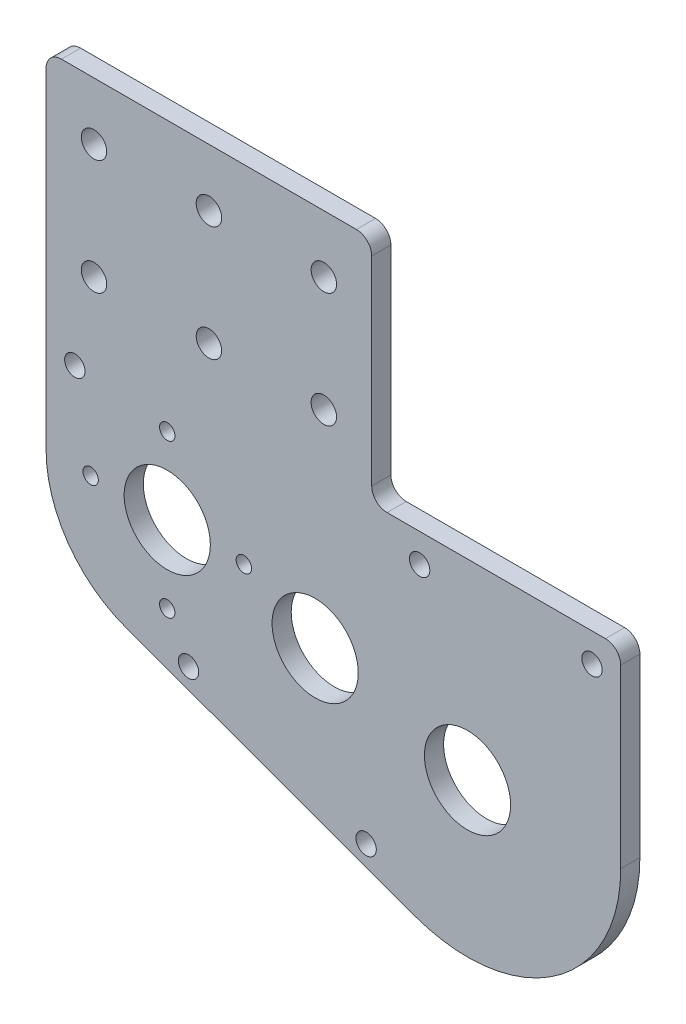
SolidWorks part; units mm, degrees
ref_plane "Front Plane" through (0, 0, 0) normal (0, 0, 1) x (1, 0, 0)
ref_plane "Top Plane" through (0, 0, 0) normal (0, 1, 0) x (1, 0, 0)
ref_plane "Right Plane" through (0, 0, 0) normal (1, 0, 0) x (0, 0, -1)
sketch "Gear&Motor Layout" plane through (0, 0, 0) normal (0, 0, 1) x (1, 0, 0)
  line L1 (-139.7, 63.5) -> (50.8, 63.5) construction
  line L2 (-99.5384, 24.9428) -> (0, 0) construction
  circle A1 centre (-99.5384, 24.9428) radius 32.2072 construction
  circle A2 centre (0, 0) radius 14.2875 construction
  circle A3 centre (-99.5384, 24.9428) radius 25.4 construction
  circle A4 centre (-124.9384, 24.9428) radius 2.5527 construction
  circle A5 centre (-99.5384, 50.3428) radius 2.5527 construction
  circle A6 centre (-74.1384, 24.9428) radius 2.5527 construction
  circle A7 centre (-99.5384, -0.4572) radius 2.5527 construction
  circle A11 centre (-50.5084, 12.6566) radius 41.91 construction
  circle A12 centre (-50.5084, 12.6566) radius 43.18 construction
  circle A15 centre (0, 0) radius 38.1 construction
  circle A16 centre (0, 0) radius 39.37 construction
  circle A17 centre (-50.5084, 12.6566) radius 13.97 construction
  circle A18 centre (-50.5084, 12.6566) radius 15.24 construction
  circle A20 centre (-99.5384, 24.9428) radius 8.89 construction
  arc A22 (-103.5384, 24.9428) -> (-95.5384, 24.9428) centre (-99.5384, 24.9428) ccw construction
  point P5 (-124.9384, 24.9428)
  point P8 (-99.5384, 50.3428)
  point P10 (-74.1384, 24.9428)
  point P14 (-99.5384, -0.4572)
  point P29 (-98.4907, 24.9428)
  point P30 (0, 0)
  point P31 (0, 0)
  point P35 (0, 0)
  point P39 (0, 0)
  point P40 (-93.0804, 49.5081)
  point P41 (0, 0)
  point P42 (0, 0)
  dimension "D4" = 83.82
  dimension "D1" = 28.575
  dimension "D3" = 50.8
  dimension "D6" = 17.78
  dimension "D7" = 86.36
  dimension "D8" = 27.94
  dimension "D9" = 30.48
  dimension "D10" = 76.2
  dimension "D11" = 78.74
  dimension "D13" = 63.5
  dimension "D14" = 5.1054
  dimension "D16" = 6.35
  dimension "D12" = 50.8
  dimension "D15" = 190.5
sketch "Sketch2" plane through (0, 0, 0) normal (0, 0, 1) x (1, 0, 0)
  line L0 (50.8, 63.5) -> (-139.7, 63.5)
  line L1 (50.8, 63.5) -> (50.8, 0)
  line L2 (-17.39, -47.7308) -> (-113.2866, -12.7923)
  line L3 (-139.7, 24.9428) -> (-139.7, 63.5)
  arc A0 (50.8, 0) -> (-17.39, -47.7308) centre (0, 0) cw
  arc A1 (-113.2866, -12.7923) -> (-139.7, 24.9428) centre (-99.5384, 24.9428) cw
extrude "Boss-Extrude1" add sketch "Sketch2" against normal blind 6.35
sketch "Sketch3" plane through (0, 0, 0) normal (0, 0, 1) x (1, 0, 0)
  line L0 (-139.7, 63.5) -> (-139.7, 139.7)
  line L1 (-139.7, 139.7) -> (-31.75, 139.7)
  line L2 (-31.75, 139.7) -> (-31.75, 63.5)
  line L5 (50.8, 0) -> (50.8, 63.5) construction
  line L6 (50.8, 63.5) -> (-139.7, 63.5) construction
  line L7 (-31.75, 63.5) -> (-139.7, 63.5)
  dimension "D1" = 82.55
  dimension "D2" = 76.2
extrude "Boss-Extrude2" add sketch "Sketch3" against normal up to surface (6.35 mm away) up to face at (-50.333, 11.5841, -6.35)
fillet "Fillet1" radius 5.08 4 edges at (50.8, 63.5, -3.175) (-31.75, 63.5, -3.175) (-31.75, 139.7, -3.175) (-139.7, 139.7, -3.175)
sketch "Sketch4" plane through (0, 0, 0) normal (0, 0, 1) x (1, 0, 0)
  circle A0 centre (0, 0) radius 14.2875 construction
  circle A1 centre (0, 0) radius 14.2875
  circle A2 centre (-50.5084, 12.6566) radius 14.2875
  circle A3 centre (-99.5384, 24.9428) radius 14.2875
  arc A4 (-103.0384, 24.9428) -> (-96.0384, 24.9428) centre (-99.5384, 24.9428) ccw construction
  point P9 (0, 0)
  dimension "D1" = 28.575
extrude "Cut-Extrude1" cut sketch "Sketch4" against normal up to next
hole_wizard "#10 Clearance Hole1" positions "Gear&Motor Layout" profile "Sketch6" hole size "#10" standard "ANSI Inch" end condition through all
sketch "Sketch6" plane through (-99.5384, -0.4572, 0) normal (1, 0, 0) x (0, -1, 0)
  line L0 (0, 0) -> (0, 6.35)
  line L1 (0, 6.35) -> (2.5527, 6.35)
  line L2 (2.5527, 6.35) -> (2.5527, 0)
  line L5 (2.5527, 0) -> (0, 0)
  line L11 (0, -6.35) -> (0, 107.95) construction
  dimension "Thru Hole Dia." = 5.1054
  dimension "Thru Hole Depth" = 6.35
hole_wizard "1/4 Clearance Hole1" positions "Sketch11" profile "Sketch9" hole size "1/4" standard "ANSI Inch" end condition through all
sketch "Sketch11" plane through (0, 0, 0) normal (0, 0, 1) x (1, 0, 0)
  line L0 (50.8, 0) -> (50.8, 58.42) construction
  line L1 (-139.7, 63.5) -> (50.8, 63.5) construction
  line L2 (-92.4826, -13.6136) -> (-33.6126, -35.062) construction
  line L4 (-113.2866, -12.7923) -> (-17.39, -47.7308) construction
  line L5 (-33.6126, -35.062) -> (-30.0888, -25.3901) construction
  line L6 (-89.5962, -5.6914) -> (-92.4826, -13.6136) construction
  line L7 (-139.7, 134.62) -> (-139.7, 24.9428) construction
  circle A0 centre (-50.5084, 12.6566) radius 43.18 construction
  circle A1 centre (0, 0) radius 39.37 construction
  circle A2 centre (-99.5384, 24.9428) radius 32.2072 construction
  point P0 (-33.6126, -35.062)
  point P2 (-92.4826, -13.6136)
  point P4 (-130.175, 53.975)
  point P6 (-15.875, 53.975)
  point P8 (41.275, 53.975)
  dimension "D1" = 9.525
  dimension "D2" = 9.525
  dimension "D3" = 6.35
  dimension "2" = 57.15
  dimension "D4" = 9.525
  dimension "D5" = 9.525
sketch "Sketch9" plane through (-33.6126, -35.062, 0) normal (1, 0, 0) x (0, -1, 0)
  line L0 (0, 0) -> (0, 6.35)
  line L1 (0, 6.35) -> (3.3782, 6.35)
  line L2 (3.3782, 6.35) -> (3.3782, 0)
  line L5 (3.3782, 0) -> (0, 0)
  line L11 (0, -6.35) -> (0, 107.95) construction
  dimension "Thru Hole Dia." = 6.7564
  dimension "Thru Hole Depth" = 6.35
sketch "Sketch12" plane through (0, 0, 0) normal (0, 0, 1) x (1, 0, 0)
  circle A0 centre (-47.625, 120.65) radius 4.2164 construction
  circle A1 centre (-47.625, 120.65) radius 4.2164
  circle A2 centre (-123.825, 120.65) radius 4.2164 construction
  circle A3 centre (-123.825, 82.55) radius 4.2164 construction
  circle A4 centre (-85.725, 82.55) radius 4.2164 construction
  circle A5 centre (-85.725, 120.65) radius 4.2164 construction
  circle A18 centre (-47.625, 82.55) radius 4.2164 construction
  circle A19 centre (-123.825, 120.65) radius 4.2164
  circle A20 centre (-123.825, 82.55) radius 4.2164
  circle A21 centre (-85.725, 82.55) radius 4.2164
  circle A22 centre (-85.725, 120.65) radius 4.2164
  circle A23 centre (-47.625, 120.65) radius 4.2164
  circle A24 centre (-47.625, 82.55) radius 4.2164
extrude "Cut-Extrude2" cut sketch "Sketch12" against normal up to surface (6.35 mm away) contours A19 | A20 | A22 | A21 | A24 | A1 up to face at (-30.2344, -35.062, -6.35)
